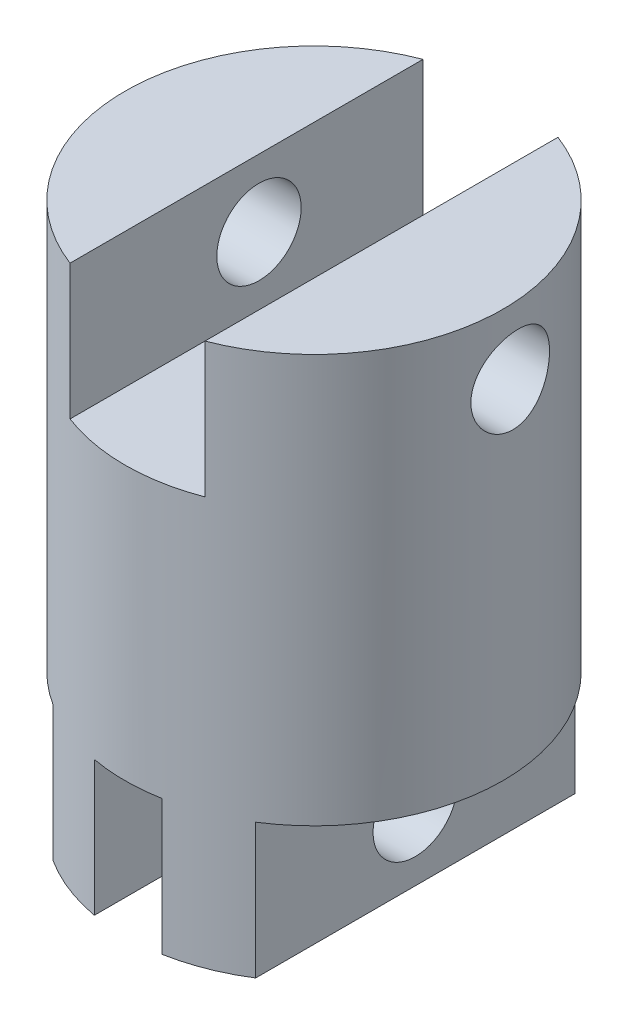
SolidWorks part; units mm, degrees
ref_plane "Front Plane" through (0, 0, 0) normal (0, 0, 1) x (1, 0, 0)
ref_plane "Top Plane" through (0, 0, 0) normal (0, 1, 0) x (1, 0, 0)
ref_plane "Right Plane" through (0, 0, 0) normal (1, 0, 0) x (0, 0, -1)
sketch "Sketch1" plane through (0, 0, 0) normal (0, 1, 0) x (1, 0, 0)
  circle A0 centre (0, 0) radius 14.224
  dimension "D1" = 28.448
extrude "Boss-Extrude1" add sketch "Sketch1" along normal blind 40.894
sketch "Sketch2" plane through (0, 40.894, 0) normal (0, 1, 0) x (1, 0, 0)
  line L0 (5.08, 13.2859) -> (5.08, -13.2859)
  line L1 (-5.08, 13.2859) -> (-5.08, -13.2859)
  arc A0 (-5.08, -13.2859) -> (5.08, -13.2859) centre (0, 0) ccw
  arc A1 (5.08, 13.2859) -> (-5.08, 13.2859) centre (0, 0) ccw
  dimension "D2" = 28.448
  dimension "D1" = 5.08
  dimension "D3" = 5.08
extrude "Cut-Extrude1" cut sketch "Sketch2" against normal blind 10.16
sketch "Sketch3" plane through (0, 0, 0) normal (0, -1, 0) x (1, 0, 0)
  line L0 (-2.54, 13.9954) -> (-2.54, -13.9954)
  line L1 (-7.62, 12.0107) -> (-7.62, -12.0107)
  line L2 (2.54, 13.9954) -> (2.54, -13.9954)
  line L3 (7.62, 12.0107) -> (7.62, -12.0107)
  arc A0 (-7.62, 12.0107) -> (-7.62, -12.0107) centre (0, 0) ccw
  arc A1 (-2.54, -13.9954) -> (2.54, -13.9954) centre (0, 0) ccw
  arc A2 (7.62, -12.0107) -> (7.62, 12.0107) centre (0, 0) ccw
  arc A3 (2.54, 13.9954) -> (-2.54, 13.9954) centre (0, 0) ccw
  dimension "D1" = 28.448
  dimension "D2" = 2.54
  dimension "D3" = 5.08
  dimension "D4" = 2.54
  dimension "D5" = 5.08
extrude "Cut-Extrude2" cut sketch "Sketch3" against normal blind 10.16
sketch "Sketch4" plane through (-5.08, 0, 0) normal (1, 0, 0) x (0, 0, -1)
  line L0 (13.2859, 40.894) -> (-13.2859, 40.894) construction
  line L5 (12.0107, 0) -> (-12.0107, 0) construction
  circle A0 centre (0.9381, 35.814) radius 3.175
  circle A2 centre (0, 5.08) radius 3.175
  point P16 (0, 0)
  dimension "D1" = 6.35
  dimension "D3" = 6.35
  dimension "D2" = 5.08
  dimension "D4" = 5.08
extrude "Cut-Extrude3" cut sketch "Sketch4" against normal through all both and the other way through all
sketch "Sketch5" plane through (0, 30.734, 0) normal (0, 1, 0) x (1, 0, 0)
  circle A0 centre (0, 0) radius 2.54
  dimension "D1" = 5.08
extrude "Cut-Extrude4" cut sketch "Sketch5" against normal through all
